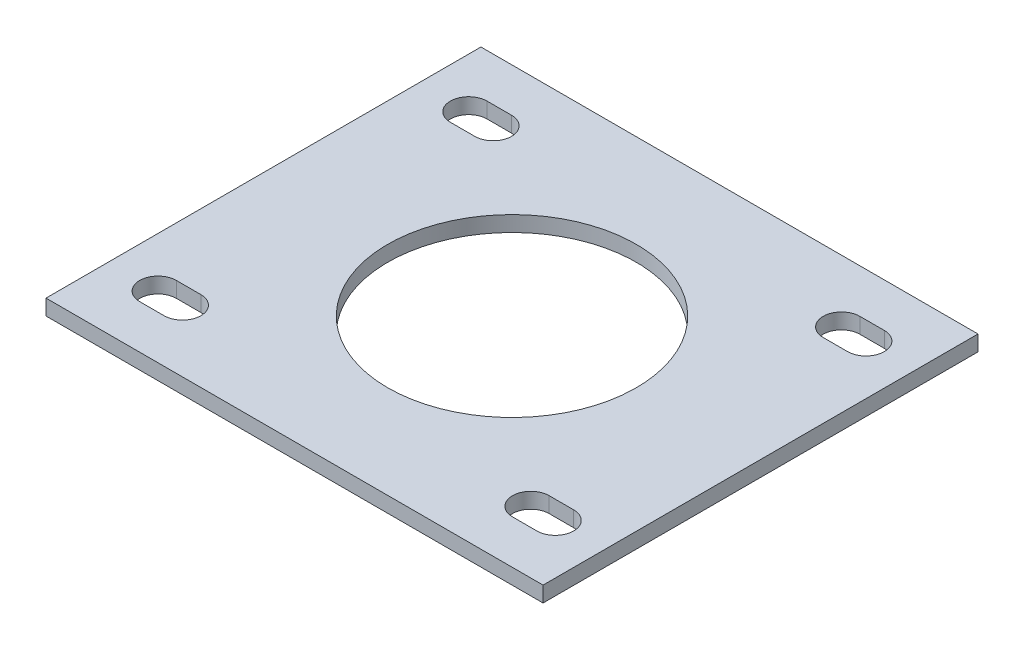
SolidWorks part; units mm, degrees
material "1023 Carbon Steel Sheet (SS)"
ref_plane "Front Plane" through (0, 0, 0) normal (0, 0, 1) x (1, 0, 0)
ref_plane "Top Plane" through (0, 0, 0) normal (0, 1, 0) x (1, 0, 0)
ref_plane "Right Plane" through (0, 0, 0) normal (1, 0, 0) x (0, 0, -1)
sketch "Sketch1" plane through (0, 0, 0) normal (0, 1, 0) x (1, 0, 0)
  line L1 (50.8, -44.45) -> (-50.8, -44.45)
  line L2 (50.8, -44.45) -> (50.8, 44.45)
  line L3 (50.8, 44.45) -> (-50.8, 44.45)
  line L4 (-50.8, -44.45) -> (-50.8, 44.45)
  line L5 (50.8, -44.45) -> (-50.8, 44.45) construction
  line L6 (50.8, 44.45) -> (-50.8, -44.45) construction
  circle A0 centre (0, 0) radius 25.4
  point P0 (0, 0)
  point P12 (0, 0)
  dimension "D3" = 50.8
  dimension "D1" = 88.9
  dimension "D2" = 101.6
extrude "Boss-Extrude1" add sketch "Sketch1" along normal blind 3.175
sketch "Sketch2" plane through (0, 3.175, 0) normal (0, 1, 0) x (1, 0, 0)
  line L0 (-40.6, 31.75) -> (-35.6, 31.75) construction
  line L1 (-40.6, 35.5) -> (-35.6, 35.5)
  line L2 (-40.6, 28) -> (-35.6, 28)
  line L3 (-38.1, 31.75) -> (-38.1, -31.75) construction
  line L4 (-40.6, -31.75) -> (-35.6, -31.75) construction
  line L5 (-40.6, -28) -> (-35.6, -28)
  line L6 (-40.6, -35.5) -> (-35.6, -35.5)
  line L7 (35.6, 31.75) -> (40.6, 31.75) construction
  line L8 (35.6, 35.5) -> (40.6, 35.5)
  line L9 (35.6, 28) -> (40.6, 28)
  line L10 (38.1, 31.75) -> (38.1, -31.75) construction
  line L11 (35.6, -31.75) -> (40.6, -31.75) construction
  line L12 (35.6, -28) -> (40.6, -28)
  line L13 (35.6, -35.5) -> (40.6, -35.5)
  line L14 (-38.1, -31.75) -> (38.1, -31.75) construction
  line L15 (-50.8, 44.45) -> (-50.8, -44.45) construction
  arc A0 (-40.6, 35.5) -> (-40.6, 28) centre (-40.6, 31.75) ccw
  arc A1 (-35.6, 28) -> (-35.6, 35.5) centre (-35.6, 31.75) ccw
  arc A2 (-40.6, -28) -> (-40.6, -35.5) centre (-40.6, -31.75) ccw
  arc A3 (-35.6, -35.5) -> (-35.6, -28) centre (-35.6, -31.75) ccw
  arc A4 (35.6, 35.5) -> (35.6, 28) centre (35.6, 31.75) ccw
  arc A5 (40.6, 28) -> (40.6, 35.5) centre (40.6, 31.75) ccw
  arc A6 (35.6, -28) -> (35.6, -35.5) centre (35.6, -31.75) ccw
  arc A7 (40.6, -35.5) -> (40.6, -28) centre (40.6, -31.75) ccw
  point P2 (-38.1, 31.75)
  point P11 (-38.1, -31.75)
  point P16 (0, -31.75)
  point P17 (-38.1, 0)
  point P21 (38.1, 31.75)
  point P30 (38.1, -31.75)
  point P35 (38.1, 0)
  dimension "D1" = 7.5
  dimension "D2" = 5
  dimension "D3" = 63.5
  dimension "D4" = 12.7
extrude "Cut-Extrude1" cut sketch "Sketch2" against normal through all
